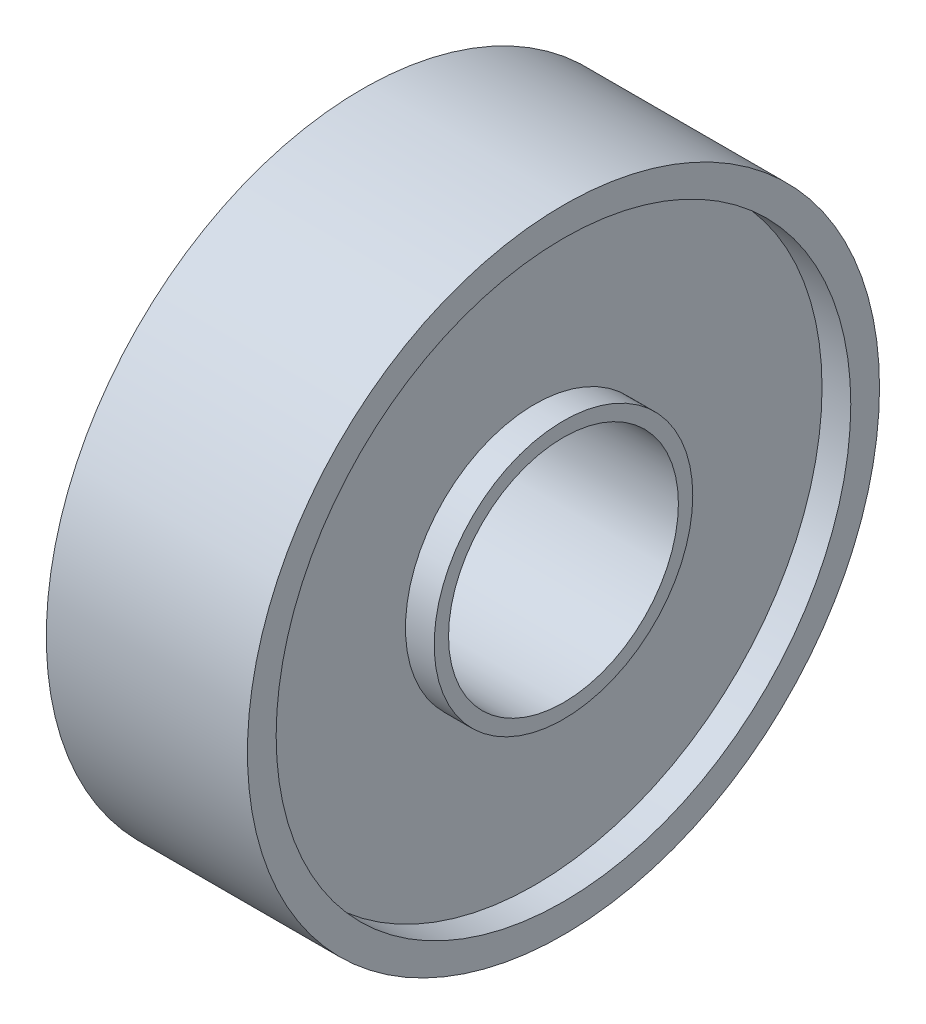
SolidWorks part; units mm, degrees
ref_plane "Alzado" through (0, 0, 0) normal (0, 0, 1) x (1, 0, 0)
ref_plane "Planta" through (0, 0, 0) normal (0, 1, 0) x (1, 0, 0)
ref_plane "Vista lateral" through (0, 0, 0) normal (1, 0, 0) x (0, 0, -1)
sketch "Croquis1" plane through (0, 0, 0) normal (1, 0, 0) x (0, 0, -1)
  circle A0 centre (0, 0) radius 11
  circle A1 centre (0, 0) radius 4
  dimension "D1" = 22
  dimension "D2" = 8
extrude "Saliente-Extruir1" add sketch "Croquis1" along normal blind 7
sketch "Croquis2" plane through (7, 0, 0) normal (1, 0, 0) x (0, 0, -1)
  circle A0 centre (0, 0) radius 10
  circle A1 centre (0, 0) radius 4.5
  dimension "D1" = 20
  dimension "D2" = 9
extrude "Cortar-Extruir1" cut sketch "Croquis2" against normal blind 1
sketch "Croquis3" plane through (0, 0, 0) normal (-1, 0, 0) x (0, 0, 1)
  circle A0 centre (0, 0) radius 10
  circle A1 centre (0, 0) radius 4.5
  dimension "D1" = 20
  dimension "D2" = 9
extrude "Cortar-Extruir2" cut sketch "Croquis3" against normal blind 1
